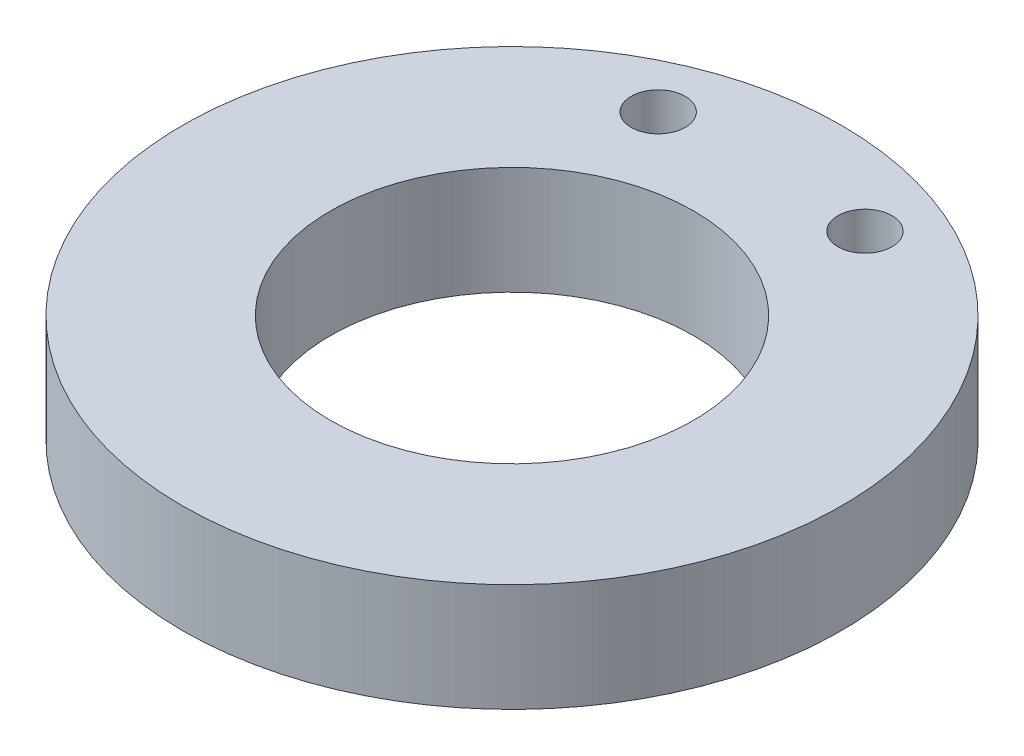
SolidWorks part; units mm, degrees
ref_plane "Front Plane" through (0, 0, 0) normal (0, 0, 1) x (1, 0, 0)
ref_plane "Top Plane" through (0, 0, 0) normal (0, 1, 0) x (1, 0, 0)
ref_plane "Right Plane" through (0, 0, 0) normal (1, 0, 0) x (0, 0, -1)
sketch "Sketch1" plane through (0, 0, 0) normal (0, 1, 0) x (1, 0, 0)
  line L0 (0, 0) -> (0, 30.5) construction
  line L1 (0, 0) -> (13.8256, 33.378) construction
  circle A0 centre (0, 0) radius 30.5
  circle A1 centre (0, 0) radius 16.8
  circle A2 centre (0, 0) radius 25 construction
  circle A3 centre (9.5671, 23.097) radius 2.5
  circle A4 centre (-9.5671, 23.097) radius 2.5
  dimension "D1" = 61
  dimension "D2" = 33.6
  dimension "D3" = 22.5
  dimension "D4" = 5
extrude "Boss-Extrude1" add sketch "Sketch1" along normal blind 10
